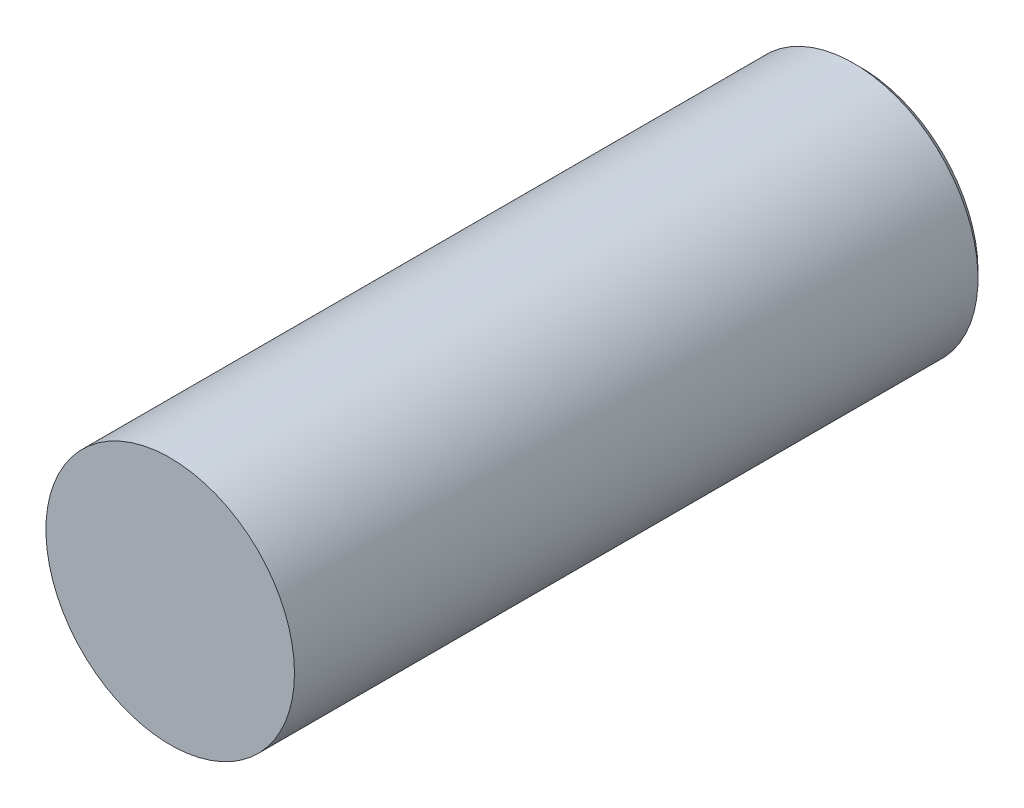
SolidWorks part; units mm, degrees
material "AISI 1045 Aço, trefilado"
ref_plane "Plano frontal" through (0, 0, 0) normal (0, 0, 1) x (1, 0, 0)
ref_plane "Plano superior" through (0, 0, 0) normal (0, 1, 0) x (1, 0, 0)
ref_plane "Plano direito" through (0, 0, 0) normal (1, 0, 0) x (0, 0, -1)
sketch "Esboço2" plane through (0, 0, 0) normal (0, 0, 1) x (1, 0, 0)
  line L0 (-3.0246, -8.4765) -> (-3.0246, -4.9765)
  line L1 (-3.0246, -4.9765) -> (2.9754, -4.9765)
  line L2 (2.9754, -4.9765) -> (2.9754, -8.494)
  line L3 (2.9754, -8.494) -> (-3.0246, -8.4765)
  line L4 (-3.0246, -8.4765) -> (2.9754, -8.494)
  arc A0 (2.9754, -8.494) -> (-3.0246, -8.4765) centre (0, 0) ccw
  dimension "D1" = 18
  dimension "D2" = 6
  dimension "D3" = 3.5
extrude "Ressalto-extrusão1" add sketch "Esboço2" along normal blind 28
sketch "Esboço3" plane through (0, 0, 28) normal (0, 0, 1) x (1, 0, 0)
  circle A0 centre (0, 0) radius 9
extrude "Ressalto-extrusão2" add sketch "Esboço3" along normal blind 22
chamfer "Chanfro2" distance 0.5 angle 45 1 edges at (0.0261, 9, 0)
